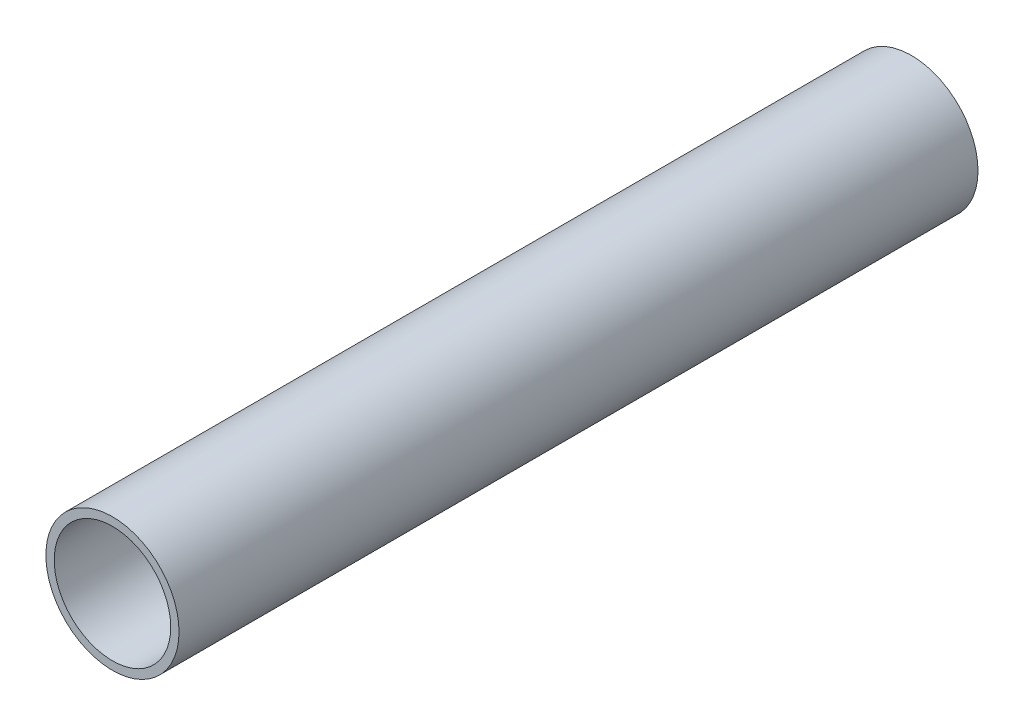
SolidWorks part; units mm, degrees
ref_plane "Front Plane" through (0, 0, 0) normal (0, 0, 1) x (1, 0, 0)
ref_plane "Top Plane" through (0, 0, 0) normal (0, 1, 0) x (1, 0, 0)
ref_plane "Right Plane" through (0, 0, 0) normal (1, 0, 0) x (0, 0, -1)
sketch "Sketch1" plane through (0, 0, 0) normal (0, 0, 1) x (1, 0, 0)
  line L0 (-25.4, 0) -> (-22.225, 0) construction
  circle A0 centre (0, 0) radius 22.225 construction
  circle A1 centre (0, 0) radius 25.4 construction
  dimension "OD" = 50.8
  dimension "ID" = 44.45
  dimension "Wall Thickness" = 3.175
sketch "Sketch2" plane through (0, 0, 0) normal (1, 0, 0) x (0, 0, -1)
  line L0 (-152.4, -25.4) -> (152.4, -25.4) construction
  point P2 (0, -25.4)
  point P3 (76.2, -25.4)
  point P4 (-76.2, -25.4)
  dimension "Length" = 304.8
  dimension "D1" = 76.2
  dimension "D2" = 76.2
sketch "Sketch3" plane through (0, 0, 0) normal (0, 0, 1) x (1, 0, 0)
  circle A0 centre (0, 0) radius 22.225 construction
  circle A1 centre (0, 0) radius 25.4 construction
  circle A2 centre (0, 0) radius 22.225
  circle A3 centre (0, 0) radius 25.4
extrude "Boss-Extrude2" add sketch "Sketch3" along normal up to vertex (152.4 mm away) and the other way up to vertex (152.4 mm away) up to point (0, -25.4, 152.4) other way up to point (0, -25.4, -152.4)
equation "\"D1@Sketch2\"=\"OD@Sketch1\"*1.5"
equation "\"D2@Sketch2\"=\"D1@Sketch2\""
